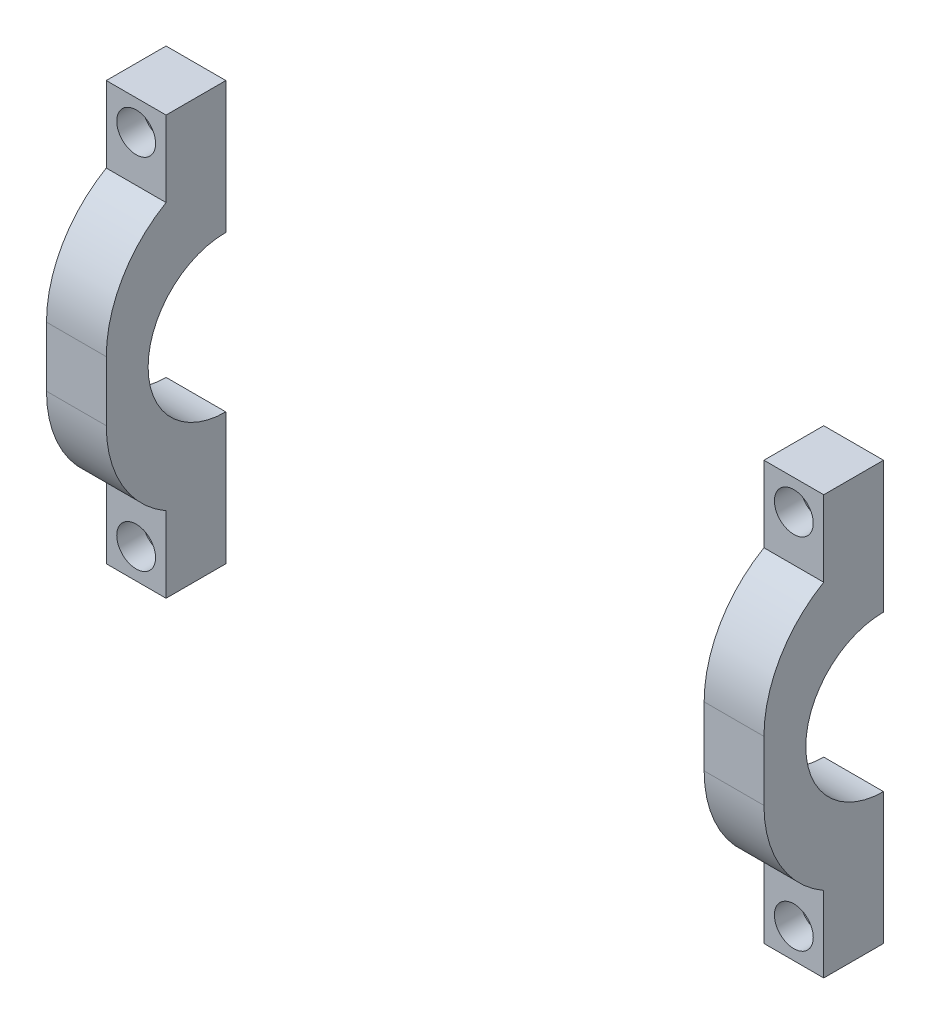
SolidWorks part; units mm, degrees
ref_plane "Ebene vorne" through (0, 0, 0) normal (0, 0, 1) x (1, 0, 0)
ref_plane "Ebene oben" through (0, 0, 0) normal (0, 1, 0) x (1, 0, 0)
ref_plane "Ebene rechts" through (0, 0, 0) normal (1, 0, 0) x (0, 0, -1)
sketch "Skizze1" plane through (0, 0, 0) normal (0, 1, 0) x (1, 0, 0)
  line L0 (-60, 0) -> (60, 0)
  line L5 (0, 0) -> (0, -46.899) construction
  line L6 (-60, 0) -> (-60, -70)
  line L7 (-60, -70) -> (-50, -70)
  line L8 (-50, -70) -> (-50, -10)
  line L9 (-50, -10) -> (50, -10)
  line L10 (50, -10) -> (50, -70)
  line L11 (50, -70) -> (60, -70)
  line L12 (60, -70) -> (60, 0)
  point P4 (0, 0)
  dimension "D1" = 120
  dimension "D2" = 10
  dimension "D3" = 10
  dimension "D4" = 70
extrude "Aufsatz-Linear austragen1" add sketch "Skizze1" along normal mid plane 50
sketch "Skizze2" plane through (0, 0, 0) normal (0, 0, -1) x (-1, 0, 0)
  line L0 (-1.533, 2.1) -> (1.533, 2.1)
  arc A0 (-1.533, 2.1) -> (1.533, 2.1) centre (0, 0) ccw
  dimension "D1" = 5.2
  dimension "D2" = 4.7
extrude "Schnitt-Linear austragen1" cut sketch "Skizze2" against normal blind 20
chamfer "Fase1" distance 10 angle 45 4 edges at (60, 0, 0) (50, 0, 10) (-60, 0, 0) (-50, 0, 10)
fillet "Verrundung1" radius 20 4 edges at (-55, -25, 70) (-55, 25, 70) (55, 25, 70) (55, -25, 70)
sketch "Skizze3" plane through (0, 0, 10) normal (0, 0, 1) x (1, 0, 0)
  line L0 (0, 0) -> (0, 12) construction
  circle A0 centre (0, 12) radius 3.25
  dimension "D2" = 6.5
  dimension "D1" = 12
extrude "Schnitt-Linear austragen2" cut sketch "Skizze3" against normal blind 3.4
sketch "Skizze4" plane through (0, 0, 6.6) normal (0, 0, 1) x (1, 0, 0)
  circle A0 centre (0, 12) radius 1.7
  dimension "D1" = 3.4
extrude "Schnitt-Linear austragen3" cut sketch "Skizze4" against normal up to surface (6.6 mm away) up to face at (0, -0.25, 0)
pattern_circular "Kreismuster1" count 3 over 360 about axis through (0, 0, 0) along (0, 0, 1) of "Schnitt-Linear austragen3", "Schnitt-Linear austragen2"
sketch "Skizze5" plane through (60, 0, 0) normal (1, 0, 0) x (0, 0, -1)
  line L0 (-50, 25) -> (-50, -25) construction
  line L2 (0, 0) -> (-70, 0) construction
  line L3 (-70, 5) -> (-70, -5) construction
  circle A0 centre (-50, 0) radius 13
  dimension "D1" = 26
extrude "Schnitt-Linear austragen4" cut sketch "Skizze5" against normal through all
sketch "Skizze7" plane through (0, 25, 0) normal (0, 1, 0) x (1, 0, 0)
  line L0 (-60, -10) -> (-60, -50) construction
  line L1 (-60, -40) -> (-50, -40)
  line L2 (-60, -40) -> (-60, -60)
  line L3 (-60, -60) -> (-50, -60)
  line L4 (-50, -40) -> (-50, -60)
  line L5 (-50, -70) -> (-50, -50) construction
  line L7 (-62.3385, -50) -> (-41.5692, -50) construction
  line L8 (-60, -50) -> (-50, -50) construction
  dimension "D1" = 20
extrude "Aufsatz-Linear austragen2" add sketch "Skizze7" along normal blind 10 and the other way blind 10
sketch "Skizze9" plane through (0, 0, 40) normal (0, 0, 1) x (1, 0, 0)
  line L0 (-50, 30) -> (-60, 30) construction
  line L1 (-50, 25) -> (-50, 35) construction
  line L2 (-60, 25) -> (-60, 35) construction
  circle A0 centre (-55, 30) radius 1.7
  dimension "D1" = 3.4
extrude "Schnitt-Linear austragen7" cut sketch "Skizze9" along normal through all
sketch "Skizze8" plane through (0, 0, 60) normal (0, 0, 1) x (1, 0, 0)
  circle A0 centre (-55, 30) radius 3.25
  circle A1 centre (-55, 30) radius 1.7 construction
  dimension "D1" = 6.5
extrude "Schnitt-Linear austragen6" cut sketch "Skizze8" against normal blind 4.4 and the other way through all
mirror "Spiegeln1" about plane through (0, 0, 0) normal (1, 0, 0) of "Schnitt-Linear austragen6", "Schnitt-Linear austragen7", "Aufsatz-Linear austragen2" second plane through (0, 0, 0) second plane normal (0, 1, 0)
sketch "Skizze6" plane through (0, 0, 0) normal (0, 1, 0) x (1, 0, 0)
  line L0 (50, 0) -> (-50, 0) construction
  line L1 (-60, 0) -> (60, 0)
  line L2 (-60, 0) -> (-60, -50)
  line L3 (-60, -50) -> (60, -50)
  line L4 (60, 0) -> (60, -50)
  line L5 (-60, -10) -> (-60, -40) construction
  line L6 (60, -40) -> (60, -10) construction
  line L7 (50, -50) -> (60, -50) construction
extrude "Schnitt-Linear austragen5" cut sketch "Skizze6" against normal through all both and the other way through all
